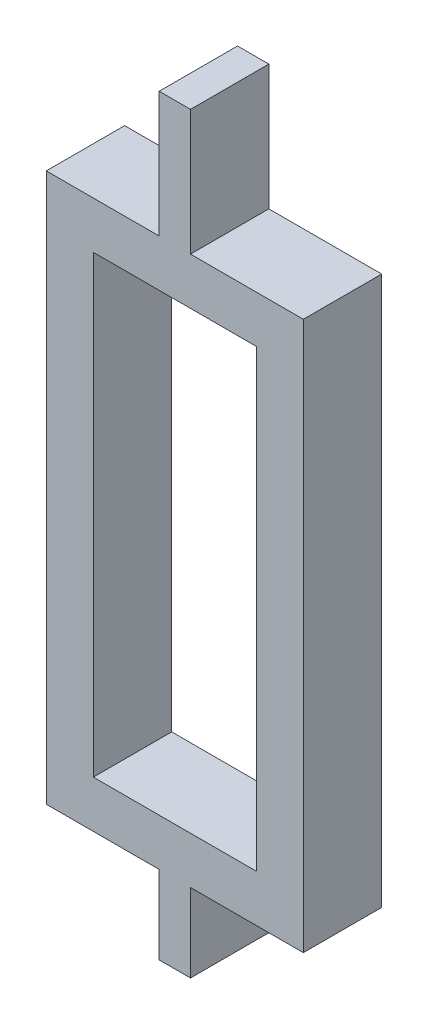
SolidWorks part; units mm, degrees
ref_plane "Front Plane" through (0, 0, 0) normal (0, 0, 1) x (1, 0, 0)
ref_plane "Top Plane" through (0, 0, 0) normal (0, 1, 0) x (1, 0, 0)
ref_plane "Right Plane" through (0, 0, 0) normal (1, 0, 0) x (0, 0, -1)
sketch "Sketch1" plane through (0, 0, 0) normal (0, 0, 1) x (1, 0, 0)
  line L1 (10.414, 0.022) -> (10.414, 44.472)
  line L3 (-10.414, 44.472) -> (-10.414, 0.022)
  line L4 (0, 0) -> (0, -6.328) construction
  line L5 (-10.414, 0.022) -> (-1.27, 0.022)
  line L6 (-1.27, 0.022) -> (-1.27, -6.328)
  line L7 (-1.27, -6.328) -> (1.27, -6.328)
  line L8 (1.27, 0.022) -> (1.27, -6.328)
  line L9 (10.414, 0.022) -> (1.27, 0.022)
  line L10 (10.414, 22.247) -> (-10.414, 22.247) construction
  line L13 (10.414, 44.472) -> (1.27, 44.472)
  line L15 (-10.414, 44.472) -> (-1.27, 44.472)
  line L16 (-1.27, 44.472) -> (-1.27, 54.632)
  line L17 (-1.27, 54.632) -> (1.27, 54.632)
  line L18 (1.27, 54.632) -> (1.27, 44.472)
  dimension "D1" = 2.54
  dimension "D2" = 44.45
  dimension "D3" = 20.828
  dimension "D4" = 6.35
  dimension "D5" = 1.27
  dimension "D6" = 10.16
  dimension "D7" = 22.247
extrude "Boss-Extrude1" add sketch "Sketch1" along normal blind 6.35
sketch "Sketch3" plane through (0, 0, 6.35) normal (0, 0, 1) x (1, 0, 0)
  line L8 (-6.604, 40.662) -> (-6.604, 3.832)
  line L9 (-6.604, 3.832) -> (6.604, 3.832)
  line L10 (6.604, 3.832) -> (6.604, 40.662)
  line L11 (6.604, 40.662) -> (-6.604, 40.662)
  line L12 (-6.604, 40.662) -> (-6.604, 3.832)
  line L14 (6.604, 3.832) -> (6.604, 40.662)
  line L16 (-6.604, 3.832) -> (6.604, 3.832)
  line L21 (6.604, 40.662) -> (-6.604, 40.662)
  dimension "D1" = 3.81
extrude "Cut-Extrude1" cut sketch "Sketch3" against normal blind 6.35 contours L12 L16 L14 L21
